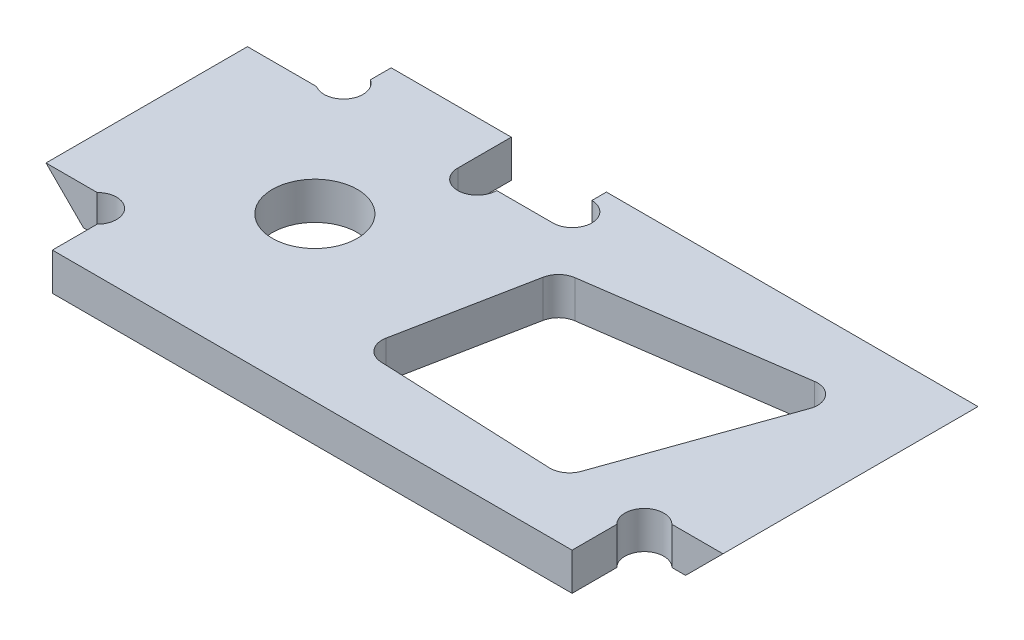
SolidWorks part; units mm, degrees
ref_plane "Front Plane" through (0, 0, 0) normal (0, 0, 1) x (1, 0, 0)
ref_plane "Top Plane" through (0, 0, 0) normal (0, 1, 0) x (1, 0, 0)
ref_plane "Right Plane" through (0, 0, 0) normal (1, 0, 0) x (0, 0, -1)
sketch "Sketch1" plane through (0, 0, 0) normal (0, 1, 0) x (1, 0, 0)
  line L0 (0, 0) -> (0, 77.1308) construction
  line L1 (-114.808, 77.1308) -> (114.808, 77.1308)
  line L2 (-114.808, 77.1308) -> (-114.808, -33.8672)
  line L3 (-114.808, -33.8672) -> (114.808, -33.8672)
  line L4 (114.808, 77.1308) -> (114.808, -33.8672)
  line L5 (-89.3342, -34.2482) -> (89.6118, -34.2482) construction
  line L6 (116.0054, 77.5118) -> (-115.7278, 77.5118) construction
  dimension "D1" = 229.616
  dimension "D2" = 0.381
  dimension "D3" = 0.381
extrude "Boss-Extrude1" add sketch "Sketch1" along normal blind 12.7
draft "Draft1" type of draft neutral plane draft angle 45 faces to draft 2 face at (-114.808, 6.35, -21.6318) face at (114.808, 6.35, -21.6318) neutral plane through (0, 12.7, 0) neutral plane normal (0, 1, 0) reverse direction yes parameters "D1"=45
sketch "Sketch2" plane through (0, 12.7, 0) normal (0, 1, 0) x (1, 0, 0)
  line L0 (-114.808, -9.3562) -> (-97.4775, -9.3562)
  line L1 (-114.808, 77.1308) -> (-114.808, -33.8672) construction
  line L2 (-88.138, -18.6956) -> (-88.138, -33.8672)
  line L3 (-114.808, -33.8672) -> (114.808, -33.8672) construction
  line L4 (-88.138, -33.8672) -> (-114.808, -33.8672)
  line L5 (-114.808, -33.8672) -> (-114.808, -9.3562)
  line L6 (0, 77.1308) -> (0, 0) construction
  line L7 (114.808, 77.1308) -> (-114.808, 77.1308) construction
  line L8 (-101.9667, -9.7372) -> (-128.9075, -9.7372) construction
  line L9 (-88.138, -18.6956) -> (-88.138, -9.3562) construction
  line L10 (-88.138, -9.3562) -> (-97.4775, -9.3562) construction
  line L11 (88.138, -9.3562) -> (97.4775, -9.3562) construction
  line L12 (88.138, -18.6956) -> (88.138, -9.3562) construction
  line L13 (114.808, -33.8672) -> (114.808, -9.3562)
  line L14 (88.138, -33.8672) -> (114.808, -33.8672)
  line L15 (88.138, -18.6956) -> (88.138, -33.8672)
  line L16 (114.808, -9.3562) -> (97.4775, -9.3562)
  line L17 (-84.6056, 59.3508) -> (-70.2806, 59.3508) construction
  line L18 (-114.808, 58.9698) -> (-91.3366, 58.9698)
  line L19 (-114.808, 58.9698) -> (-114.808, 77.1308)
  line L20 (-114.808, 77.1308) -> (-84.2246, 77.1308)
  line L21 (-84.2246, 70.0996) -> (-84.2246, 77.1308)
  line L23 (-84.6056, 59.3508) -> (-84.6056, 72.0508) construction
  line L24 (-84.2246, 70.0996) -> (-84.2246, 58.9698) construction
  line L25 (-84.2246, 58.9698) -> (-91.3366, 58.9698) construction
  arc A0 (-88.138, -18.6956) -> (-97.4775, -9.3562) centre (-92.8077, -14.0259) ccw
  arc A1 (88.138, -18.6956) -> (97.4775, -9.3562) centre (92.8077, -14.0259) cw
  arc A2 (-91.3366, 58.9698) -> (-84.2246, 70.0996) centre (-87.7806, 64.5347) ccw
  dimension "D2" = 6.604
  dimension "D6" = 6.604
  dimension "D1" = 0.381
  dimension "D3" = 26.67
  dimension "D4" = 0.381
  dimension "D5" = 0.381
  dimension "D7" = 7.112
extrude "Cut-Extrude1" cut sketch "Sketch2" against normal through all
sketch "Sketch3" plane through (0, 12.7, 0) normal (0, 1, 0) x (1, 0, 0)
  line L4 (114.808, -9.3562) -> (114.808, 77.1308) construction
  line L5 (114.808, 77.1308) -> (-84.2246, 77.1308) construction
  line L6 (-88.138, -33.8672) -> (88.138, -33.8672) construction
  line L8 (-88.138, -33.8672) -> (88.138, -33.8672) construction
  line L9 (-68.1559, 77.1308) -> (-68.1559, -33.8672) construction
  line L10 (-68.1559, 21.6318) -> (-114.808, 21.6318) construction
  line L11 (-114.808, 58.9698) -> (-114.808, -9.3562) construction
  line L12 (-11.9927, 16.9328) -> (-49.9785, 16.9328) construction
  line L13 (3.048, 41.3852) -> (-5.6909, -3.1372)
  line L14 (79.7107, 56.8108) -> (8.5944, 46.6508)
  line L15 (66.548, -9.1591) -> (86.868, 48.0633)
  line L16 (0.508, -11.0072) -> (60.0432, -13.5472)
  arc A5 (60.0432, -13.5472) -> (66.548, -9.1591) centre (60.3247, -6.9492) ccw
  arc A6 (0.508, -11.0072) -> (-5.6909, -3.1372) centre (0.7895, -4.4092) cw
  arc A7 (8.5944, 46.6508) -> (3.048, 41.3852) centre (9.5283, 40.1132) ccw
  arc A8 (86.868, 48.0633) -> (79.7107, 56.8108) centre (80.6447, 50.2732) ccw
  dimension "D1" = 20.32
  dimension "D2" = 48.26
  dimension "D8" = 6.604
  dimension "D3" = 27.94
  dimension "D4" = 20.32
  dimension "D5" = 22.86
  dimension "D6" = 114.3
  dimension "D7" = 30.48
  dimension "D9" = 111.76
extrude "Cut-Extrude2" cut sketch "Sketch3" against normal through all
sketch "Sketch4" plane through (0, 0, 0) normal (0, -1, 0) x (1, 0, 0)
  line L0 (-88.138, 33.8672) -> (88.138, 33.8672) construction
  line L5 (-11.601, -59.3508) -> (-11.601, -72.0508) construction
  line L6 (-43.097, -59.3508) -> (-43.097, -72.0508) construction
  line L7 (-11.601, -59.3508) -> (-43.097, -59.3508) construction
  line L8 (-76.0504, 33.8672) -> (-76.0504, -77.1308) construction
  line L9 (102.108, -77.1308) -> (-84.2246, -77.1308) construction
  line L10 (-76.0504, -21.6318) -> (-114.808, -21.6318) construction
  line L11 (-114.808, -58.9698) -> (-114.808, 9.3562) construction
  line L12 (-43.478, -77.1308) -> (-43.478, -58.9698)
  line L13 (-11.22, -58.9698) -> (-30.27, -58.9698)
  line L14 (-11.22, -77.1308) -> (-11.22, -72.1778)
  line L15 (-11.22, -77.1308) -> (-43.478, -77.1308)
  line L16 (114.808, -77.1308) -> (-84.2246, -77.1308) construction
  arc A2 (-43.478, -58.9698) -> (-30.27, -58.9698) centre (-36.874, -58.9698) cw
  arc A3 (-11.22, -58.9698) -> (-11.22, -72.1778) centre (-11.22, -65.5738) cw
  dimension "D4" = 6.604
  dimension "D1" = 0.381
  dimension "D2" = 0.381
  dimension "D3" = 0.381
extrude "Cut-Extrude3" cut sketch "Sketch4" against normal through all
sketch "Sketch5" plane through (0, 0, 0) normal (0, -1, 0) x (1, 0, 0)
  circle A0 centre (-54.2628, -21.2861) radius 14.4061
extrude "Cut-Extrude4" cut sketch "Sketch5" against normal through all
